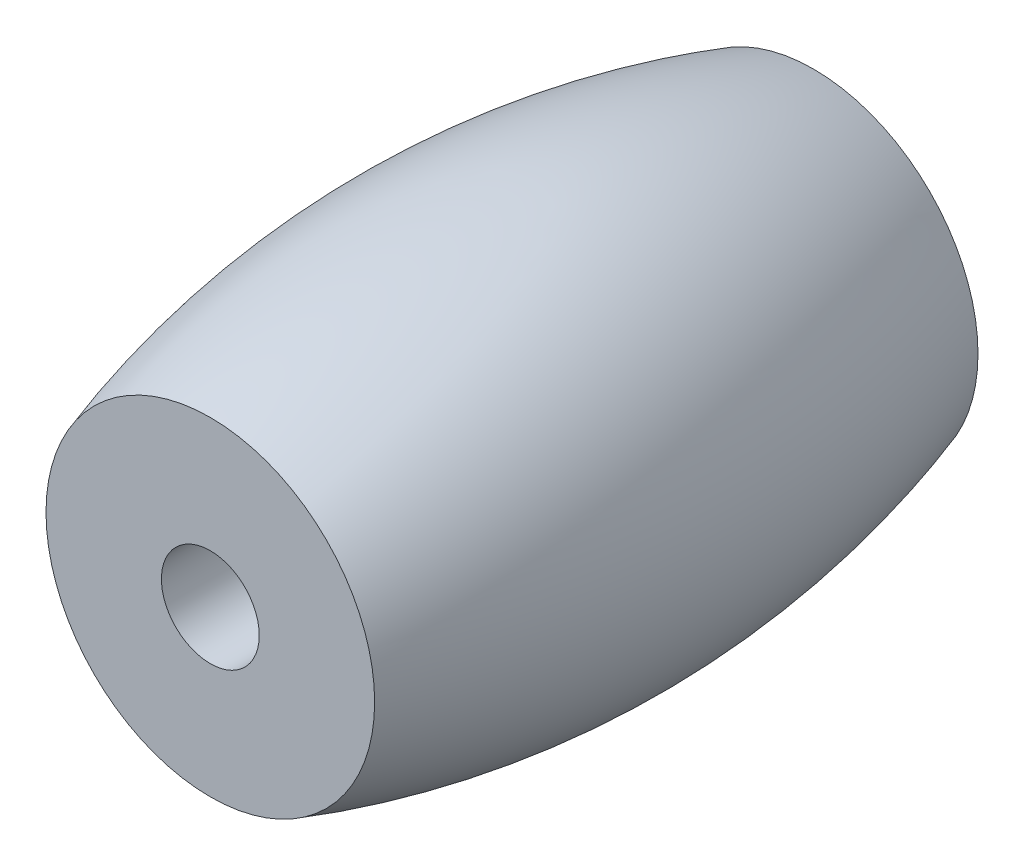
SolidWorks part; units mm, degrees
ref_plane "前视基准面" through (0, 0, 0) normal (0, 0, 1) x (1, 0, 0)
ref_plane "上视基准面" through (0, 0, 0) normal (0, 1, 0) x (1, 0, 0)
ref_plane "右视基准面" through (0, 0, 0) normal (1, 0, 0) x (0, 0, -1)
sketch "草图2" plane through (0, 0, 0) normal (0, 1, 0) x (1, 0, 0)
  line L0 (0, 0) -> (0, 31.9233) construction
  line L1 (1.5, 0) -> (1.5, 18.5)
  line L2 (1.5, 18.5) -> (5.0384, 18.5)
  line L3 (1.5, 0) -> (5.0384, 0)
  line L4 (5.0384, 18.5) -> (5.0384, 0) construction
  line L5 (5.0384, 9.25) -> (-26.8547, 9.25) construction
  line L6 (5.0384, 9.25) -> (6.5, 9.25) construction
  arc A0 (5.0384, 18.5) -> (5.0384, 0) centre (-23.5, 9.25) cw
  dimension "D5" = 30
  dimension "D1" = 1.5
  dimension "D2" = 18.5
  dimension "D3" = 6.5
revolve "旋转1" add sketch "草图2" angle 360 about L0
